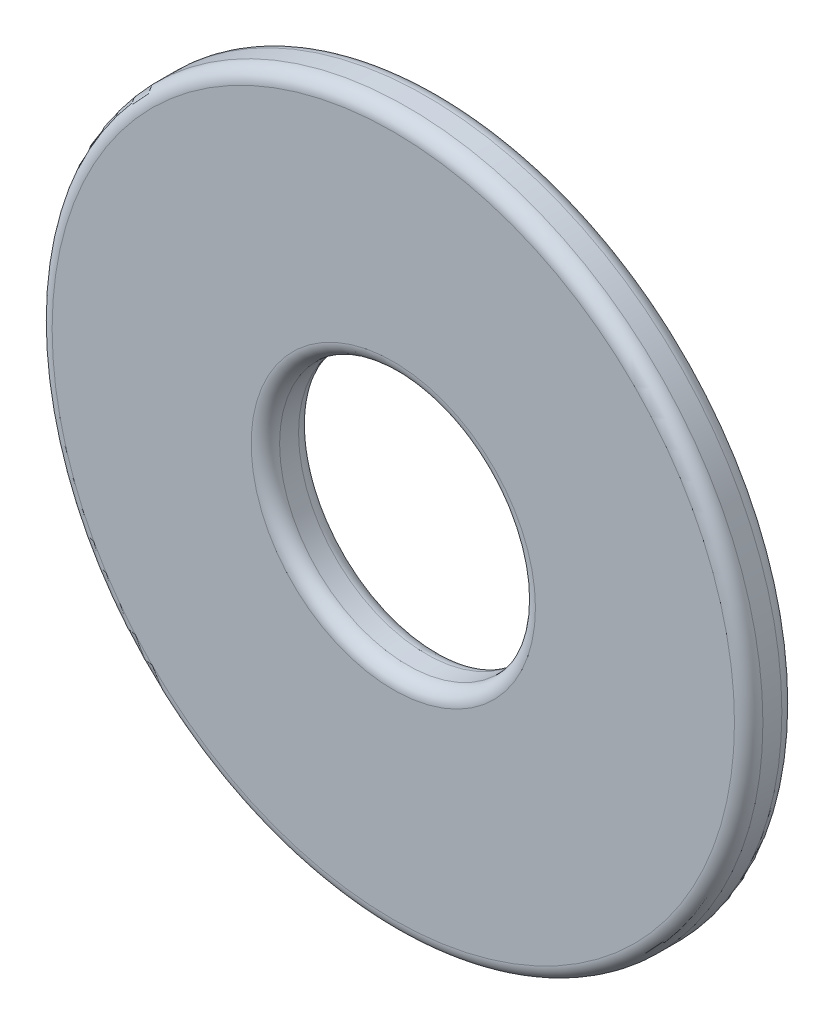
SolidWorks part; units mm, degrees
ref_plane "Plano frontal" through (0, 0, 0) normal (0, 0, 1) x (1, 0, 0)
ref_plane "Plano superior" through (0, 0, 0) normal (0, 1, 0) x (1, 0, 0)
ref_plane "Plano direito" through (0, 0, 0) normal (1, 0, 0) x (0, 0, -1)
sketch "Esboço1" plane through (0, 0, 0) normal (0, 0, 1) x (1, 0, 0)
  circle A0 centre (0, 0) radius 2.7
  circle A1 centre (0, 0) radius 7.5
  dimension "D1" = 5.4
  dimension "D2" = 15
extrude "Ressalto-extrusão1" add sketch "Esboço1" along normal blind 1
fillet "Filete1" radius 0.3 4 edges at (2.7, 0, 0) (7.5, 0, 0) (2.7, 0, 1) (7.5, 0, 1)
